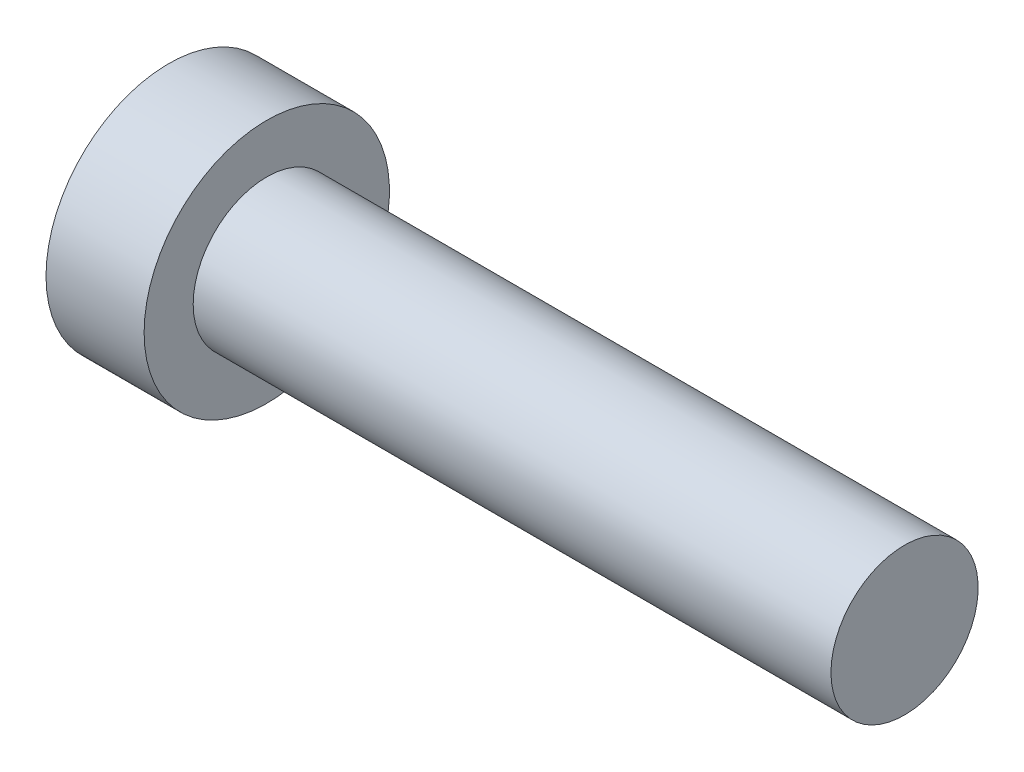
SolidWorks part; units mm, degrees
ref_plane "Front Plane" through (0, 0, 0) normal (0, 0, 1) x (1, 0, 0)
ref_plane "Top Plane" through (0, 0, 0) normal (0, 1, 0) x (1, 0, 0)
ref_plane "Right Plane" through (0, 0, 0) normal (1, 0, 0) x (0, 0, -1)
sketch "Sketch1" plane through (0, 0, 0) normal (0, 0, 1) x (1, 0, 0)
  line L0 (0, 0) -> (30, 0)
  line L1 (30, 0) -> (30, 3)
  line L2 (30, 3) -> (4, 3)
  line L3 (4, 3) -> (4, 5)
  line L4 (4, 5) -> (0, 5)
  line L5 (0, 5) -> (0, 0)
  dimension "D1" = 5
  dimension "D2" = 4
  dimension "D3" = 3
  dimension "D4" = 30
revolve "Revolve1" add sketch "Sketch1" angle 360 about L0
sketch "Sketch2" plane through (0, 0, 0) normal (-1, 0, 0) x (0, 0, 1)
  line L1 (2.8868, 0) -> (1.4434, 2.5)
  line L2 (1.4434, 2.5) -> (-1.4434, 2.5)
  line L3 (-1.4434, 2.5) -> (-2.8868, 0)
  line L4 (-2.8868, 0) -> (-1.4434, -2.5)
  line L5 (-1.4434, -2.5) -> (1.4434, -2.5)
  line L6 (1.4434, -2.5) -> (2.8868, 0)
  circle A0 centre (0, 0) radius 2.5 construction
  dimension "D1" = 5
extrude "Cut-Extrude1" cut sketch "Sketch2" against normal blind 2.38
